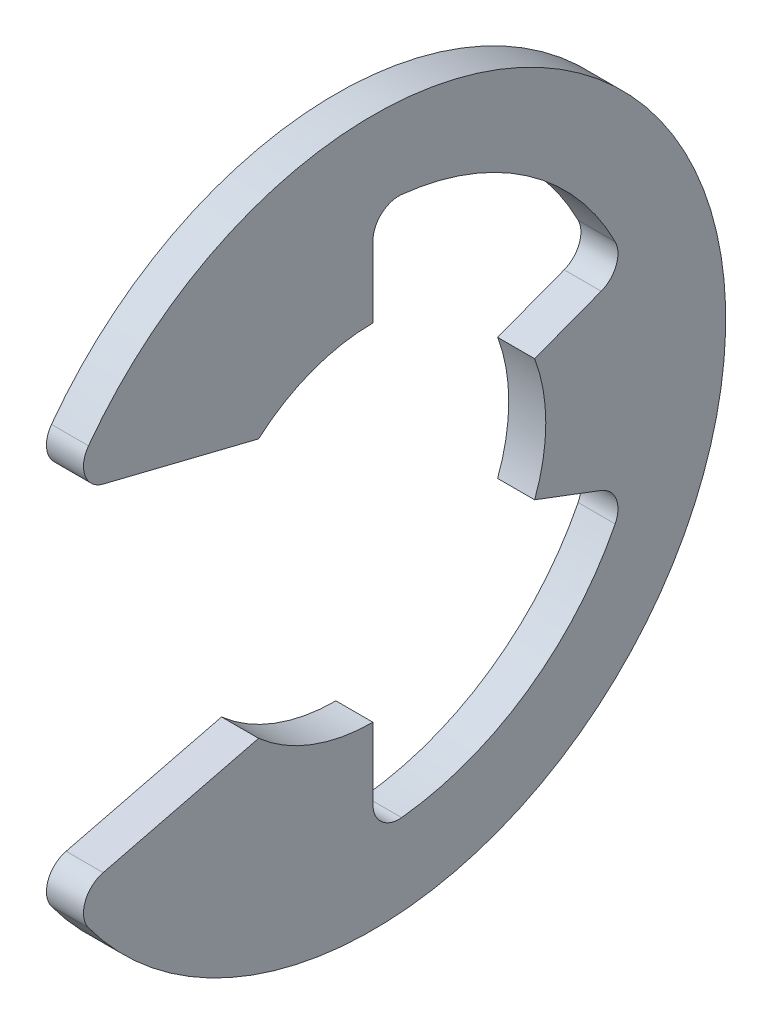
SolidWorks part; units mm, degrees
material "AISI 1020"
ref_plane "Front" through (0, 0, 0) normal (0, 0, 1) x (1, 0, 0)
ref_plane "Top" through (0, 0, 0) normal (0, 1, 0) x (1, 0, 0)
ref_plane "Right" through (0, 0, 0) normal (1, 0, 0) x (0, 0, -1)
sketch "Sketch1" plane through (0, 0, 0) normal (1, 0, 0) x (0, 0, -1)
  line L0 (-8.7883, -5.0981) -> (-3.2929, -3.7338)
  line L1 (-8.7883, 5.0981) -> (-3.2929, 3.7338)
  line L2 (0, -4.9784) -> (0, -7.8134)
  line L3 (0, 4.9784) -> (0, 7.8134)
  line L4 (4.6569, -1.7601) -> (7.3087, -2.7624)
  line L5 (4.6569, 1.7601) -> (7.3087, 2.7624)
  line L6 (0, 0) -> (-10.414, 0) construction
  line L7 (4.6569, 1.7601) -> (4.6569, -1.7601) construction
  line L8 (0, -4.9784) -> (-3.2929, -3.7338) construction
  line L9 (0, 10.16) -> (0, -10.16) construction
  circle A1 centre (0, 0) radius 10.414 construction
  circle A2 centre (0, 0) radius 4.9784 construction
  arc A3 (-8.7883, -5.0981) -> (-8.7883, 5.0981) centre (0, 0) ccw
  arc A4 (-3.2929, -3.7338) -> (0, -4.9784) centre (0, 0) ccw
  arc A5 (-3.2929, 3.7338) -> (0, 4.9784) centre (0, 0) cw
  arc A6 (4.6569, 1.7601) -> (4.6569, -1.7601) centre (0, 0) cw
  arc A7 (0, -7.8134) -> (7.3087, -2.7624) centre (0, 0) ccw
  arc A8 (7.3087, 2.7624) -> (0, 7.8134) centre (0, 0) ccw
  dimension "D" = 9.9568
  dimension "D1" = 7.8134
  dimension "OD" = 20.32
  dimension "D2" = 5.6607
  dimension "D3" = 7.4676
extrude "Extrude1" add sketch "Sketch1" along normal mid plane 1.0668
fillet "Fillet1" radius 0.7468 6 edges at (0, -7.8134, 0) (0, 7.8134, 0) (0, -5.0981, 8.7883) (0, 5.0981, 8.7883) (0, -2.7624, -7.3087) (0, 2.7624, -7.3087)
sketch "Sketch3" plane through (0, 0, 0) normal (0, 1, 0) x (1, 0, 0)
  line L0 (0.5842, 6.35) -> (0.5842, 5.0292)
  line L1 (0.5842, 5.0292) -> (-0.5842, 5.0292)
  line L2 (-0.5842, 5.0292) -> (-0.5842, 6.35)
  line L3 (-0.5842, 6.35) -> (-12.5603, 6.35)
  line L4 (4.9657, 0) -> (4.9657, 5.6896)
  line L5 (-12.5603, 6.35) -> (-12.5603, 0)
  line L6 (-12.5603, 0) -> (4.9657, 0)
  line L8 (4.9657, 0) -> (4.9657, 6.35) construction
  line L9 (4.9657, 6.35) -> (0.5842, 6.35) construction
  line L10 (4.9657, 0) -> (17.2631, 0) construction
  line L11 (4.9657, 5.6896) -> (4.3053, 6.35)
  line L12 (4.3053, 6.35) -> (0.5842, 6.35)
  point P2 (0, 5.0292)
  point P5 (0.5842, 5.6896)
  dimension "D2" = 17.526
  dimension "D1" = 4.3815
  dimension "D3" = 45
revolve "Revolve2" [suppressed] add sketch "Sketch3" angle 360 about L10
equation "\"D2@Sketch3\" = \"W@Sketch3\"*15"
equation "\"D1@Sketch3\" = \"D2@Sketch3\"/4"
equation "\"D1@Sketch1\" = (\"OD@Sketch1\"+\"D@Sketch1\")/3.875"
equation "\"D3@Sketch1\" = \"D@Sketch1\"*.75"
equation "\"D1@Fillet1\" = \"D1@Extrude1\"*.7"
